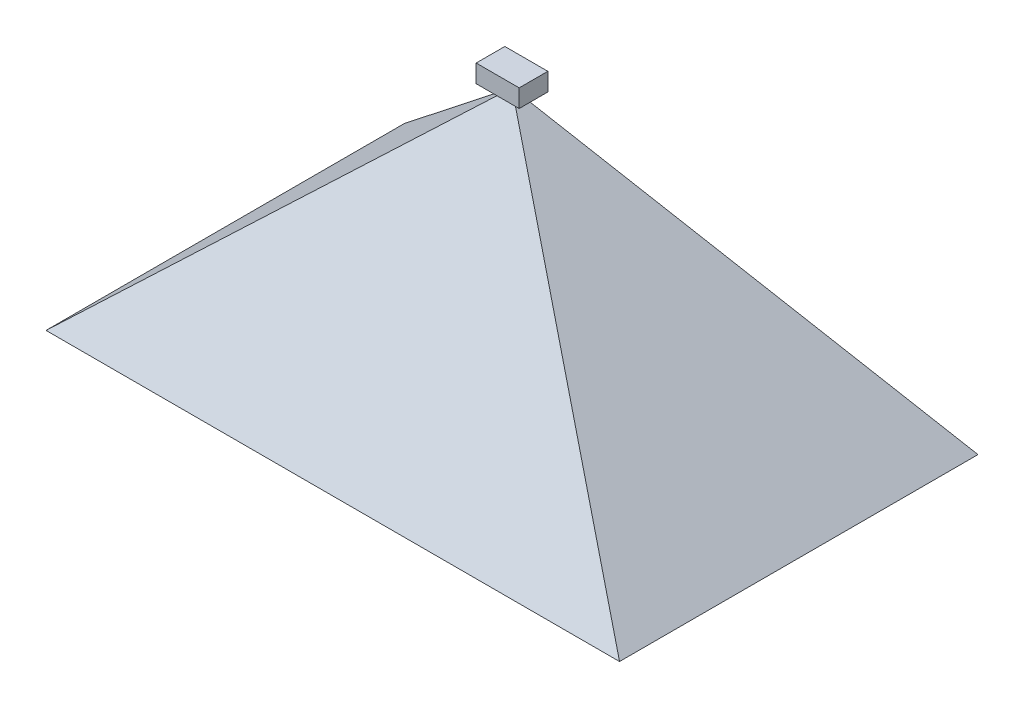
SolidWorks part; units mm, degrees
ref_plane "Front Plane" through (0, 0, 0) normal (0, 0, 1) x (1, 0, 0)
ref_plane "Top Plane" through (0, 0, 0) normal (0, 1, 0) x (1, 0, 0)
ref_plane "Right Plane" through (0, 0, 0) normal (1, 0, 0) x (0, 0, -1)
ref_plane "distance of measurement" through (0, 90.932, 0) normal (0, 1, 0) x (1, 0, 0)
sketch "Sketch1" plane through (0, 0, 0) normal (0, 1, 0) x (1, 0, 0)
  line L1 (-101.6, -63.5) -> (101.6, -63.5)
  line L2 (-101.6, -63.5) -> (-101.6, 63.5)
  line L3 (-101.6, 63.5) -> (101.6, 63.5)
  line L4 (101.6, -63.5) -> (101.6, 63.5)
  line L5 (-101.6, -63.5) -> (101.6, 63.5) construction
  line L6 (-101.6, 63.5) -> (101.6, -63.5) construction
  point P0 (0, 0)
sketch "Sketch2" plane through (0, 90.932, 0) normal (0, 1, 0) x (1, 0, 0)
  line L0 (-101.6, -63.5) -> (101.6, 63.5) construction
  line L1 (-2.7554, -1.7221) -> (2.7554, -1.7221)
  line L2 (-2.7554, -1.7221) -> (-2.7554, 1.7221)
  line L3 (-2.7554, 1.7221) -> (2.7554, 1.7221)
  line L4 (2.7554, -1.7221) -> (2.7554, 1.7221)
  line L5 (-2.7554, -1.7221) -> (2.7554, 1.7221) construction
  line L6 (-2.7554, 1.7221) -> (2.7554, -1.7221) construction
  point P0 (0, 0)
loft "FOV" add profiles "Sketch2", "Sketch1"
ref_point "centre of lens"
sketch "Sketch3" plane through (0, 90.932, 0) normal (0, 1, 0) x (1, 0, 0)
  circle A0 centre (0, 0) radius 2.54
extrude "camera lens" add sketch "Sketch3" along normal blind 2.54
sketch "Sketch4" plane through (0, 93.472, 0) normal (0, 1, 0) x (1, 0, 0)
  line L1 (7.62, 5.08) -> (-7.62, 5.08)
  line L2 (7.62, 5.08) -> (7.62, -5.08)
  line L3 (7.62, -5.08) -> (-7.62, -5.08)
  line L4 (-7.62, 5.08) -> (-7.62, -5.08)
  line L5 (7.62, 5.08) -> (-7.62, -5.08) construction
  line L6 (7.62, -5.08) -> (-7.62, 5.08) construction
  point P0 (0, 0)
  dimension "D1" = 15.24
  dimension "D2" = 10.16
extrude "camera body" add sketch "Sketch4" along normal blind 6.35
ref_point "centre of rays"
sketch3d "ray"
  line L0 (0, 99.822, 0) -> (-26.2774, -31.7447, 17.4035)
